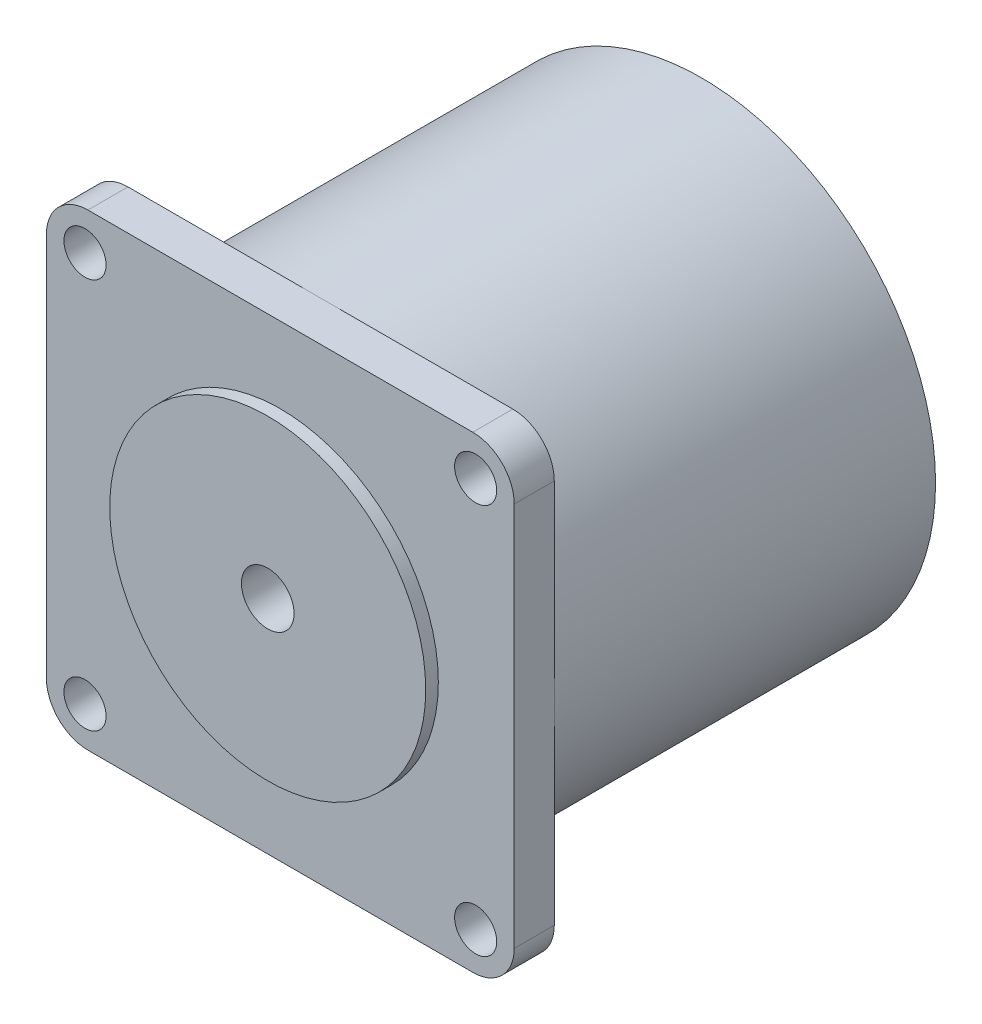
SolidWorks part; units mm, degrees
ref_plane "Plan1" through (0, 0, 0) normal (0, 0, 1) x (1, 0, 0)
ref_plane "Plan2" through (0, 0, 0) normal (0, 1, 0) x (1, 0, 0)
ref_plane "Plan3" through (0, 0, 0) normal (1, 0, 0) x (0, 0, -1)
sketch "Esquisse1" plane through (0, 0, 0) normal (0, 0, 1) x (1, 0, 0)
  circle A0 centre (0, 0) radius 28.2
  dimension "D1" = 56.4
extrude "Base-Extrusion" add sketch "Esquisse1" along normal blind 45.97
sketch "Esquisse2" plane through (0, 0, 45.97) normal (0, 0, 1) x (1, 0, 0)
  line L0 (-23.2, 28.2) -> (23.2, 28.2)
  line L1 (-28.2, 23.2) -> (-28.2, -23.2)
  line L2 (23.2, -28.2) -> (-23.2, -28.2)
  line L3 (28.2, -23.2) -> (28.2, 23.2)
  arc A0 (-23.2, 28.2) -> (-28.2, 23.2) centre (-23.2, 23.2) ccw
  arc A1 (-28.2, -23.2) -> (-23.2, -28.2) centre (-23.2, -23.2) ccw
  arc A2 (28.2, -23.2) -> (23.2, -28.2) centre (23.2, -23.2) cw
  arc A3 (28.2, 23.2) -> (23.2, 28.2) centre (23.2, 23.2) ccw
  dimension "D5" = 5
  dimension "D6" = 5
  dimension "D7" = 5
  dimension "D8" = 5
  dimension "D1" = 56.4
  dimension "D2" = 56.4
  dimension "D3" = 28.2
  dimension "D4" = 28.2
extrude "Boss.-Extru.1" add sketch "Esquisse2" along normal blind 4.83
sketch "Esquisse3" plane through (0, 0, 50.8) normal (0, 0, 1) x (1, 0, 0)
  circle A0 centre (0, 0) radius 19.05
  dimension "D1" = 38.1
extrude "Boss.-Extru.2" add sketch "Esquisse3" along normal blind 1.52
sketch "Esquisse4" plane through (0, 0, 50.8) normal (0, 0, 1) x (1, 0, 0)
  circle A0 centre (-23.55, 23.55) radius 2.54
  circle A4 centre (0, 0) radius 19.05 construction
  dimension "D1" = 5.08
  dimension "D2" = 23.55
  dimension "D9" = 23.55
extrude "Enlèv. mat.-Extru.1" cut sketch "Esquisse4" against normal through all
sketch "Esquisse5" plane through (0, 0, 52.32) normal (0, 0, 1) x (1, 0, 0)
  circle A0 centre (0, 0) radius 3.175
  dimension "D1" = 6.35
extrude "Enlèv. mat.-Extru.2" cut sketch "Esquisse5" against normal blind 30
pattern_linear "Répétition linéaire1" count 2 spacing 47.1 count 2 spacing 47.1
